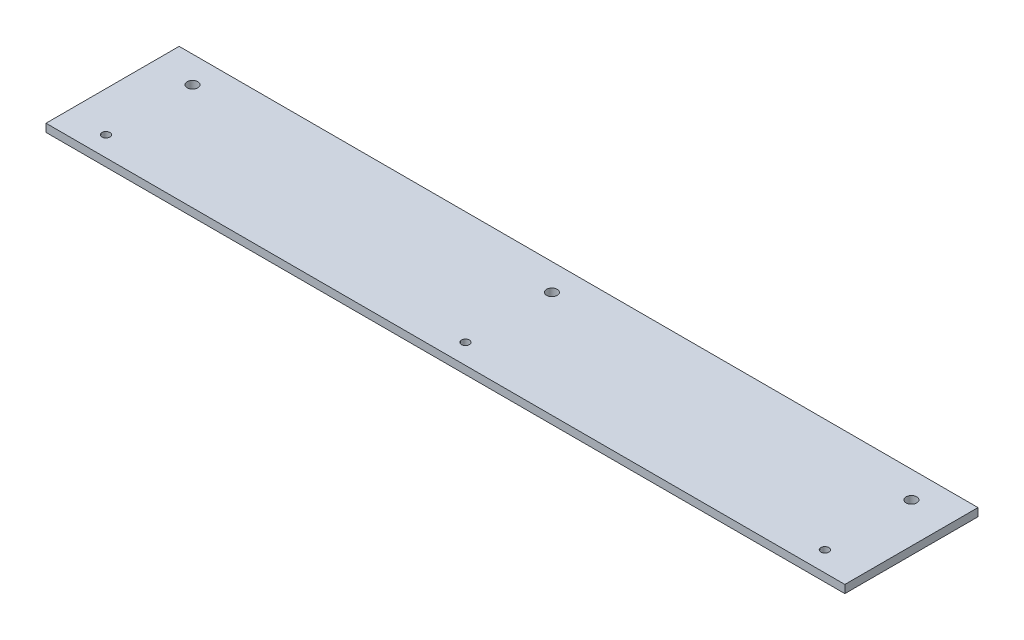
SolidWorks part; units mm, degrees
ref_plane "Front Plane" through (0, 0, 0) normal (0, 0, 1) x (1, 0, 0)
ref_plane "Top Plane" through (0, 0, 0) normal (0, 1, 0) x (1, 0, 0)
ref_plane "Right Plane" through (0, 0, 0) normal (1, 0, 0) x (0, 0, -1)
sketch "Sketch1" plane through (0, 0, 0) normal (0, 1, 0) x (1, 0, 0)
  line L0 (0, 15) -> (300, 15) construction
  line L1 (0, 0) -> (300, 0)
  line L2 (0, 0) -> (0, 50)
  line L3 (0, 50) -> (300, 50)
  line L4 (300, 0) -> (300, 50)
  circle A0 centre (15, 40) radius 2
  circle A1 centre (150, 40) radius 2
  circle A2 centre (285, 40) radius 2
  circle A3 centre (15, 7.5) radius 1.5
  circle A4 centre (150, 7.5) radius 1.5
  circle A5 centre (285, 7.5) radius 1.5
  point P19 (150, 6.4629)
  point P20 (15, 7.5)
  point P21 (0, 0)
  point P22 (150, 7.5)
  point P23 (0, 0)
  point P24 (0, 0)
  dimension "D4" = 4
  dimension "D9" = 3
  dimension "D1" = 50
  dimension "D2" = 300
  dimension "D3" = 15
  dimension "D5" = 135
  dimension "D6" = 135
  dimension "D7" = 15
  dimension "D8" = 10
  dimension "D10" = 7.5
extrude "Boss-Extrude1" add sketch "Sketch1" along normal blind 3
